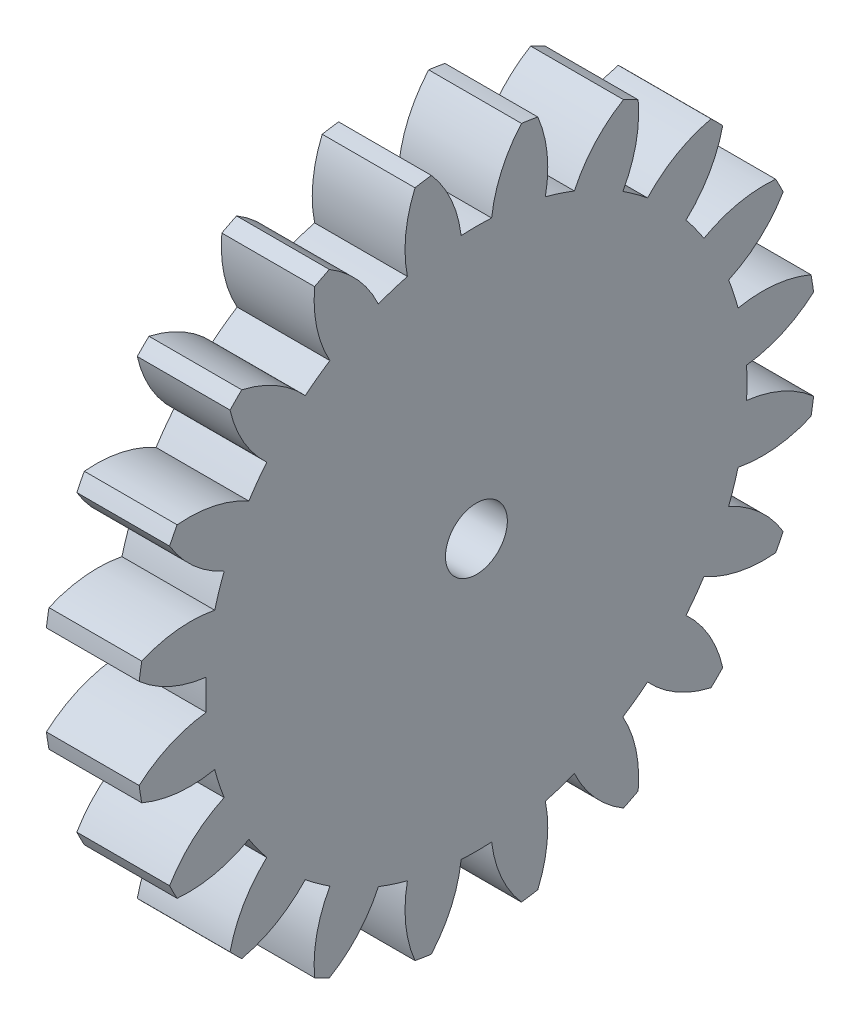
SolidWorks part; units mm, degrees
ref_plane "Plane1" through (0, 0, 0) normal (0, 0, 1) x (1, 0, 0)
ref_plane "Plane2" through (0, 0, 0) normal (0, 1, 0) x (1, 0, 0)
ref_plane "Plane3" through (0, 0, 0) normal (1, 0, 0) x (0, 0, -1)
sketch "HoldingSke" plane through (0, 0, 0) normal (0, 1, 0) x (1, 0, 0)
  line L0 (0, 0) -> (0.4698, -0.171)
  line L1 (-15, 0) -> (100, 0) construction
  line L2 (0, 0) -> (-2.1039, 2.3779)
  line L3 (0, 0) -> (-11.863, 4.5341)
  line L4 (0, 0) -> (8.1152, 2.9537)
  line L5 (0, 0) -> (-46.8476, -17.4728)
  line L6 (0, 0) -> (-4.9738, -3.3558)
  line L7 (-2.1039, 2.3779) -> (8.6586, 51.2059)
  line L8 (-76.2, 54.61) -> (-75.5, 54.61)
  line L9 (-71.009, 38.7566) -> (-53.1078, 45.2721)
  line L10 (-76.2, 71.12) -> (104.1128, 71.12)
  line L11 (0, 0) -> (-6, 0)
  line L12 (-76.2, 101.6) -> (-76.133, 101.6)
  line L13 (24.9733, 27.94) -> (52.9518, 28.4284)
  line L14 (24.9733, 27.94) -> (24.9743, 27.94)
  line L15 (24.9733, 27.94) -> (100.4006, 29.5858)
  line L16 (-63.627, -2) -> (-12.827, -2)
  circle A0 centre (0, 0) radius 2
  circle A1 centre (0, 0) radius 17.499
  circle A2 centre (0, 0) radius 37.5
  circle A3 centre (0, 0) radius 2
  dimension "MHD" = 34.998
  dimension "Hub_dia" = 75
  dimension "Bore" = 4
  dimension "MBD" = 4
  dimension "Num_teeth" = 20
  dimension "Pitch" = 0.5
  dimension "Overall_len" = 50
  dimension "Show_teeth" = 20
  dimension "Thickness" = 6
  dimension "OAL" = 50.0001
  dimension "T_dim" = 0.7
  dimension "Ap" = 20
  dimension "H" = 19.05
  dimension "Pitch_radius" = 180.3128
  dimension "Width" = 6
  dimension "Backlash" = 0.067
  dimension "Addendum_fac" = 1
  dimension "Dedendum_fac" = 1.25
  dimension "Clearance_fac" = 0.25
  dimension "Dedendum_add" = 0.001
  dimension "Module" = 2
sketch "BasProSke" plane through (0, 0, 0) normal (0, 1, 0) x (1, 0, 0)
  line L0 (-10, 0) -> (60, 0) construction
  line L1 (0, 0) -> (0, 22)
  line L2 (0, 0) -> (6, 0)
  line L3 (6, 0) -> (6, 22)
  line L4 (6, 22) -> (0, 22)
  dimension "Thickness" = 6
  dimension "Diameter" = 44
revolve "Base-Revolve" add sketch "BasProSke" angle 360 about L0
sketch "TooCutSke" plane through (0, 0, 0) normal (1, 0, 0) x (0, 0, -1)
  line L1 (0, 0) -> (0, 107) construction
  line L2 (0, 0) -> (-1.6864, 19.9288) construction
  line L3 (0, 0) -> (-6.2409, 39.4033) construction
  line L4 (-1.6864, 19.9288) -> (-3.1204, 19.7016) construction
  arc A0 (0.9862, 17.4712) -> (-0.9862, 17.4712) centre (0, 0) ccw
  arc A1 (2.9329, 21.8293) -> (-2.9329, 21.8293) centre (0, 0) ccw
  circle A2 centre (0, 0) radius 20 construction
  circle A3 centre (0, 0) radius 18.7939 construction
  arc A4 (-0.9862, 17.4712) -> (-2.9329, 21.8293) centre (-8.9313, 16.536) ccw
  arc A5 (2.9329, 21.8293) -> (0.9862, 17.4712) centre (8.9313, 16.536) ccw
  dimension "Root_dia" = 34.998
  dimension "Overcut_dia" = 44.0508
  dimension "Pitch_dia" = 40
  dimension "Base_dia" = 37.5877
  dimension "Flank_rad" = 8
  dimension "Half_ang" = 9
  dimension "Half_CT" = 1.4519
extrude "ToothCut" cut sketch "TooCutSke" along normal through all
fillet "Breaks" [suppressed] radius 0.04
fillet "RootFillets" [suppressed] radius 0.501
pattern_circular "TeethCuts" count 20 every 18 about axis through (-10, 0, 0) along (1, 0, 0) of "ToothCut", "RootFillets", "Breaks"
sketch "HubNeaOneSke" plane through (0, 0, 0) normal (-1, 0, 0) x (0, 0, 1)
  circle A0 centre (0, 0) radius 17.499
  dimension "Diameter" = 34.998
extrude "HubNearOne" [suppressed] add sketch "HubNeaOneSke" along normal blind 44.0001
sketch "HubNeaBotSke" plane through (0, 0, 0) normal (-1, 0, 0) x (0, 0, 1)
  circle A0 centre (0, 0) radius 17.499
  dimension "Diameter" = 34.998
extrude "HubNearBoth" [suppressed] add sketch "HubNeaBotSke" along normal blind 22
ref_plane "FarPln" through (6, 0, 0) normal (1, 0, 0) x (0, 0, -1)
sketch "HubFarSke" plane through (6, 0, 0) normal (1, 0, 0) x (0, 0, -1)
  circle A0 centre (0, 0) radius 17.499
  dimension "Diameter" = 34.998
extrude "HubFar" [suppressed] add sketch "HubFarSke" along normal blind 22
sketch "BorSke" plane through (0, 0, 0) normal (1, 0, 0) x (0, 0, -1)
  circle A0 centre (0, 0) radius 2
  dimension "Diameter" = 4
extrude "Bore" cut sketch "BorSke" along normal mid plane 100.0001
sketch "KeySke" plane through (0, 0, 0) normal (1, 0, 0) x (0, 0, -1)
  line L0 (-0.8, 0) -> (-0.8, 2.7)
  line L1 (-0.8, 2.7) -> (0.8, 2.7)
  line L2 (0.8, 2.7) -> (0.8, 0)
  line L3 (0, 0) -> (0, 34) construction
  line L4 (-0.8, 0) -> (0.8, 0)
  dimension "Offset" = 2.7
  dimension "Width" = 1.6
extrude "Keyway" [suppressed] cut sketch "KeySke" along normal mid plane 100.0001
pattern_circular "Keyway2" [suppressed] count 2 every 90 about axis through (-10, 0, 0) along (1, 0, 0)
equation "' \"Module@HoldingSke\" = 6.35"
equation "' \"Num_teeth@HoldingSke\" = 12"
equation "' \"Ap@HoldingSke\" =  20"
equation "' \"Ap@HoldingSke\" = 20"
equation "' \"Width@HoldingSke\" = 0.5 * 25.4"
equation "' \"Hub_dia@HoldingSke\"= 1 * 25.4"
equation "' \"Hub_dia@HoldingSke\" = 1 * 25.4"
equation "' \"Overall_len@HoldingSke\" = 1.0 * 25.4"
equation "' \"Bore@HoldingSke\" = 0.75 * 25.4"
equation "' \"T_dim@HoldingSke\" = 0.1 * 25.4"
equation "' \"Width@KeySke\" = 0.25 * 25.4"
equation "' \"Show_teeth@HoldingSke\" = 13"
equation "' \"Backlash@HoldingSke\" = 0.009 * 25.4"
equation "' \"Addendum_fac@HoldingSke\" = 1.0"
equation "' \"Dedendum_fac@HoldingSke\" = 1.25"
equation "' \"Dedendum_add@HoldingSke\" = 0.00005 * 25.4"
equation "' \"Clearance_fac@HoldingSke\" = 0.25"
equation "\"Pitch@HoldingSke\" = 1 / \"Module@HoldingSke\""
equation "\"Overcut_dia@TooCutSke\" = (\"Num_teeth@HoldingSke\" + 2 * \"Addendum_fac@HoldingSke\") / \"Pitch@HoldingSke\" + 0.002 * 25.4"
equation "\"Pitch_dia@TooCutSke\" = \"Num_teeth@HoldingSke\" / \"Pitch@HoldingSke\""
equation "\"Base_dia@TooCutSke\" = \"Num_teeth@HoldingSke\" / \"Pitch@HoldingSke\" * cos((\"Ap@HoldingSke\"  * 3.14159265 / 180))"
equation "\"Root_dia@TooCutSke\" = (\"Num_teeth@HoldingSke\" + 2) / \"Pitch@HoldingSke\" - 2 * (\"Addendum_fac@HoldingSke\" + \"Dedendum_fac@HoldingSke\") / \"Pitch@HoldingSke\" - \"Dedendum_add@HoldingSke\" * 2"
equation "\"Half_ang@TooCutSke\" = 180 / \"Num_teeth@HoldingSke\""
equation "\"Half_CT@TooCutSke\" = \"Num_teeth@HoldingSke\" / \"Pitch@HoldingSke\" * sin((3.14159265 / 2 / \"Num_teeth@HoldingSke\")) / 2 - 7 * \"Backlash@HoldingSke\" / 4"
equation "\"Flank_rad@TooCutSke\" = \"Num_teeth@HoldingSke\" / \"Pitch@HoldingSke\" / 5"
equation "\"Radius@RootFillets\" = \"Clearance_fac@HoldingSke\" / \"Pitch@HoldingSke\" + \"Dedendum_add@HoldingSke\""
equation "\"Break_rad@Breaks\" = 0.02 / \"Pitch@HoldingSke\""
equation "\"Thickness@HoldingSke\" = \"Width@HoldingSke\""
equation "\"OAL@HoldingSke\" = \"Thickness@HoldingSke\""
equation "\"MHD@HoldingSke\" = (\"Num_teeth@HoldingSke\" + 2) / \"Pitch@HoldingSke\" - 2 * (\"Addendum_fac@HoldingSke\" + \"Dedendum_fac@HoldingSke\")  / \"Pitch@HoldingSke\" - \"Dedendum_add@HoldingSke\" * 2"
equation "\"MBD@HoldingSke\" = (\"Num_teeth@HoldingSke\" + 2) / \"Pitch@HoldingSke\" - 2 * (\"Addendum_fac@HoldingSke\" + \"Dedendum_fac@HoldingSke\")  / \"Pitch@HoldingSke\" - \"Dedendum_add@HoldingSke\" * 2 - 0.002 * 25.4"
equation "\"MHD@HoldingSke\" = ((sgn( \"MHD@HoldingSke\" - \"Hub_dia@HoldingSke\" )-1)*( \"MHD@HoldingSke\" - \"Hub_dia@HoldingSke\" ))/-2+ \"Hub_dia@HoldingSke\""
equation "\"MBD@HoldingSke\" = ((sgn( \"MBD@HoldingSke\" - \"Bore@HoldingSke\" )-1)*( \"MBD@HoldingSke\" - \"Bore@HoldingSke\" ))/-2+ \"Bore@HoldingSke\""
equation "\"OAL@HoldingSke\" = ((sgn( \"OAL@HoldingSke\" - \"Overall_len@HoldingSke\" )+1)*( \"OAL@HoldingSke\" - \"Overall_len@HoldingSke\" ))/2 + \"Overall_len@HoldingSke\" + 0.000002 * 25.4"
equation "\"Num_teeth@TeethCuts\" = int( \"Show_teeth@HoldingSke\" ) + 1"
equation "\"Num_teeth@TeethCuts\" = ((sgn( \"Num_teeth@TeethCuts\" - \"Num_teeth@HoldingSke\" )-1)*( \"Num_teeth@TeethCuts\" - \"Num_teeth@HoldingSke\" ))/-2+ \"Num_teeth@HoldingSke\""
equation "\"Num_teeth@TeethCuts\" = ((sgn( \"Num_teeth@TeethCuts\" - 2.0)+1)*( \"Num_teeth@TeethCuts\" - 2.0))/2 +2.0"
equation "\"Angle@TeethCuts\" = 360.0 / \"Num_teeth@HoldingSke\""
equation "\"Diameter@BasProSke\" = (\"Num_teeth@HoldingSke\" + 2 * \"Addendum_fac@HoldingSke\") / \"Pitch@HoldingSke\""
equation "\"Thickness@BasProSke\"  = \"Thickness@HoldingSke\""
equation "' \"Fillet_rad@BasProSke\" =  \"Thickness@HoldingSke\" * 0.05"
equation "' \"Fillet_rad@BasProSke\" = \"Thickness@HoldingSke\" * 0.05"
equation "\"MHD@HoldingSke\" = ((sgn( \"MHD@HoldingSke\" - \"Root_dia@TooCutSke\" )-1)*( \"MHD@HoldingSke\" - \"Root_dia@TooCutSke\" ))/-2+ \"Root_dia@TooCutSke\""
equation "\"Diameter@HubNeaOneSke\" = \"MHD@HoldingSke\""
equation "\"Length@HubNearOne\" = \"OAL@HoldingSke\" - \"Thickness@BasProSke\""
equation "\"Diameter@HubNeaBotSke\" = \"MHD@HoldingSke\""
equation "\"Length@HubNearBoth\" = ( \"OAL@HoldingSke\" - \"Thickness@BasProSke\" ) / 2.0"
equation "\"Thickness@FarPln\" = \"Thickness@BasProSke\""
equation "\"Diameter@HubFarSke\" = \"MHD@HoldingSke\""
equation "\"Length@HubFar\" = ( \"OAL@HoldingSke\" - \"Thickness@BasProSke\" ) / 2.0"
equation "\"Diameter@BorSke\" = \"MBD@HoldingSke\""
equation "\"D1@Bore\" = \"OAL@HoldingSke\" * 2.0"
equation "\"D1@Keyway\" = \"OAL@HoldingSke\" * 2.0"
equation "\"Offset@KeySke\" = \"T_dim@HoldingSke\" + \"MBD@HoldingSke\" / 2.0"
